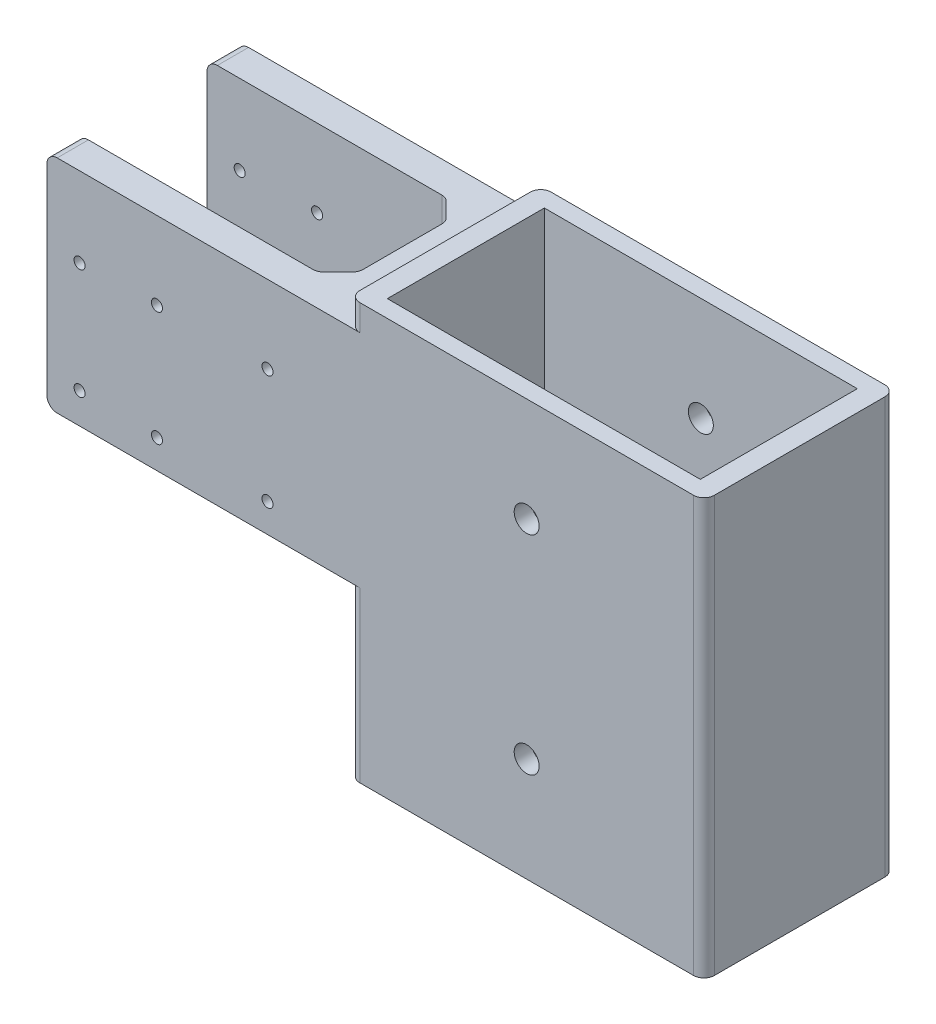
SolidWorks part; units mm, degrees
ref_plane "Front Plane" through (0, 0, 0) normal (0, 0, 1) x (1, 0, 0)
ref_plane "Top Plane" through (0, 0, 0) normal (0, 1, 0) x (1, 0, 0)
ref_plane "Right Plane" through (0, 0, 0) normal (1, 0, 0) x (0, 0, -1)
sketch "Sketch1" plane through (0, 0, 0) normal (0, 0, 1) x (1, 0, 0)
  line L0 (-45.9066, 14) -> (0, 14) construction
  line L1 (-53.9066, 47) -> (-53.9066, -7)
  line L3 (106.614, -48.25) -> (106.614, 53.35)
  line L7 (-53.9066, -7) -> (20, -7)
  line L8 (20, -7) -> (20, -48.25)
  line L9 (20, -48.25) -> (106.614, -48.25)
  line L10 (-53.9066, 47) -> (20, 47)
  line L11 (20, 47) -> (20, 53.35)
  line L12 (20, 53.35) -> (106.614, 53.35)
  circle A0 centre (0, 0) radius 1.35
  circle A1 centre (-27, 0) radius 1.35
  circle A2 centre (-45.9066, 0.5) radius 1.35
  circle A3 centre (-45.9066, 27.5) radius 1.35
  circle A4 centre (-27, 28) radius 1.35
  circle A5 centre (0, 28) radius 1.35
  dimension "D1" = 2.7
  dimension "D2" = 28
  dimension "D3" = 27
  dimension "D4" = 27
  dimension "D5" = 18.9066
  dimension "D6" = 8
  dimension "D7" = 19.5
  dimension "D8" = 7.5
  dimension "D9" = 20
  dimension "D10" = 86.614
  dimension "D11" = 101.6
  dimension "D12" = 6.35
extrude "Boss-Extrude1" add sketch "Sketch1" along normal blind 46.736
sketch "Sketch2" plane through (0, 53.35, 0) normal (0, 1, 0) x (1, 0, 0)
  line L0 (-53.9066, -7.62) -> (4.5134, -7.62)
  line L1 (25.08, -42.545) -> (101.534, -42.545)
  line L2 (25.08, -42.545) -> (25.08, -4.191)
  line L3 (25.08, -4.191) -> (101.534, -4.191)
  line L4 (101.534, -42.545) -> (101.534, -4.191)
  line L5 (25.08, -42.545) -> (101.534, -4.191) construction
  line L6 (25.08, -4.191) -> (101.534, -42.545) construction
  line L7 (-53.9066, -46.736) -> (-53.9066, 0) construction
  line L10 (4.5134, -39.116) -> (-53.9066, -39.116)
  line L11 (-53.9066, -39.116) -> (-53.9066, -7.62)
  line L12 (4.5134, -7.62) -> (9.5934, -12.7)
  line L13 (9.5934, -12.7) -> (9.5934, -34.036)
  line L14 (9.5934, -34.036) -> (4.5134, -39.116)
  line L15 (20, -46.736) -> (20, 0) construction
  line L16 (106.614, -23.368) -> (101.534, -23.368) construction
  line L17 (106.614, -46.736) -> (106.614, 0) construction
  line L18 (20, 0) -> (-53.9066, 0) construction
  point P0 (63.307, -23.368)
  point P17 (9.5934, -23.368)
  dimension "D1" = 38.354
  dimension "D2" = 76.454
  dimension "D3" = 5.08
  dimension "D4" = 7.62
  dimension "D5" = 58.42
  dimension "D6" = 5.08
  dimension "D7" = 225
extrude "Cut-Extrude1" cut sketch "Sketch2" against normal blind 137.16
fillet "Fillet1" radius 2.54 14 edges at (106.614, 2.55, 0) (106.614, 2.55, 46.736) (4.5134, 20, 39.116) (9.5934, 20, 34.036) (9.5934, 20, 12.7) (4.5134, 20, 7.62) (20, 50.175, 0) (20, 50.175, 46.736) (20, -27.625, 0) (20, -27.625, 46.736) (-53.9066, -7, 42.926) (-53.9066, -7, 3.81) (-53.9066, 47, 3.81) (-53.9066, 47, 42.926)
sketch "Sketch3" plane through (0, 0, 46.736) normal (0, 0, 1) x (1, 0, 0)
  line L0 (63.307, 53.35) -> (63.307, 27.95) construction
  line L1 (104.074, 53.35) -> (22.54, 53.35) construction
  line L2 (22.54, -48.25) -> (104.074, -48.25) construction
  circle A0 centre (63.307, 27.95) radius 3.05
  circle A1 centre (63.307, -22.85) radius 3.05
  dimension "D1" = 6.1
  dimension "D2" = 25.4
  dimension "D3" = 25.4
extrude "Cut-Extrude2" cut sketch "Sketch3" against normal blind 66.294
